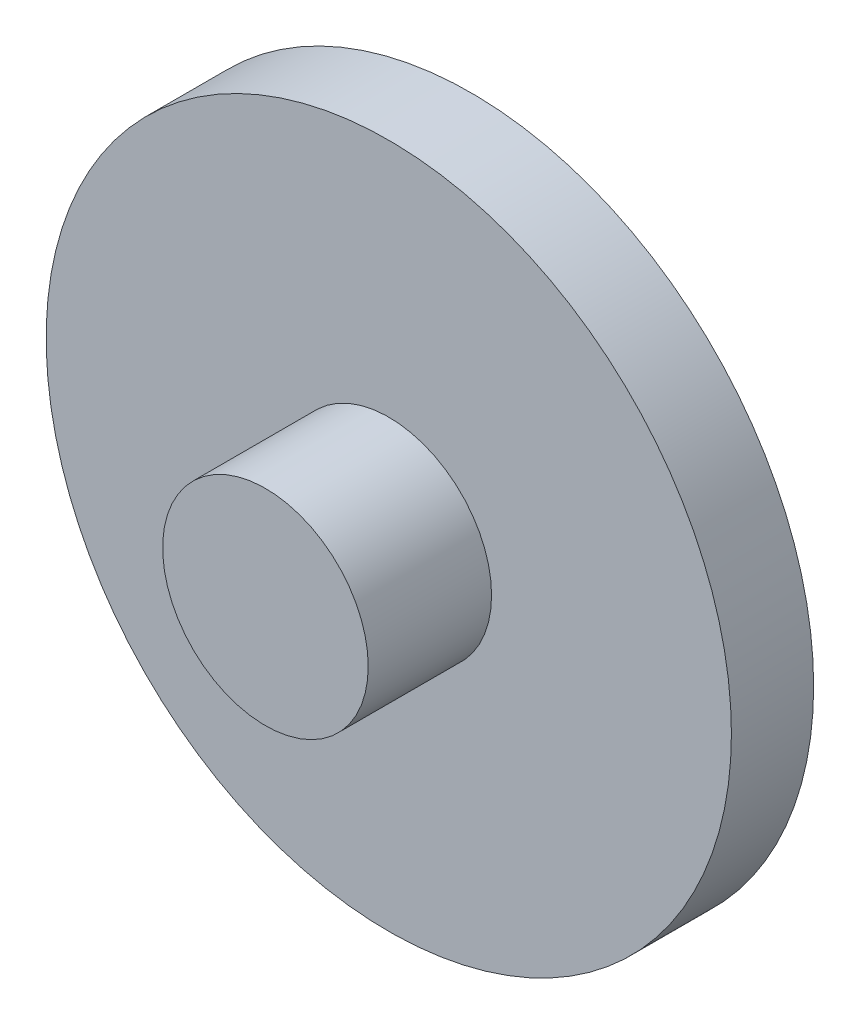
SolidWorks part; units mm, degrees
ref_plane "Front Plane" through (0, 0, 0) normal (0, 0, 1) x (1, 0, 0)
ref_plane "Top Plane" through (0, 0, 0) normal (0, 1, 0) x (1, 0, 0)
ref_plane "Right Plane" through (0, 0, 0) normal (1, 0, 0) x (0, 0, -1)
sketch "草图3" plane through (0, 0, 0) normal (0, 0, 1) x (1, 0, 0)
  circle A0 centre (75, 12) radius 50
  dimension "diameter" = 100
  dimension "x" = 75
  dimension "y" = 12
extrude "BaseDisc" add sketch "草图3" along normal blind 12
sketch "草图4" plane through (0, 0, 12) normal (0, 0, 1) x (1, 0, 0)
  circle A0 centre (75, 12) radius 15
  dimension "diameter" = 30
  dimension "x" = 75
  dimension "y" = 12
extrude "PivotBoss" add sketch "草图4" along normal blind 18
